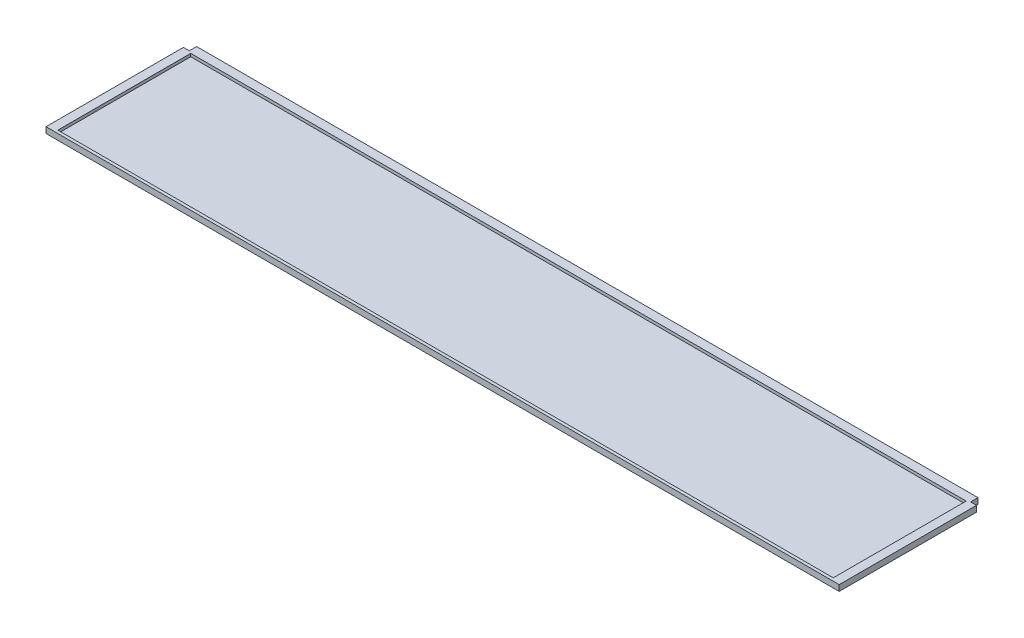
SolidWorks part; units mm, degrees
material "Beech"
ref_plane "Front Plane" through (0, 0, 0) normal (0, 0, 1) x (1, 0, 0)
ref_plane "Top Plane" through (0, 0, 0) normal (0, 1, 0) x (1, 0, 0)
ref_plane "Right Plane" through (0, 0, 0) normal (1, 0, 0) x (0, 0, -1)
sketch "Sketch1" plane through (0, 0, 0) normal (0, 1, 0) x (1, 0, 0)
  line L1 (-118.2851, 60.9681) -> (418.7149, 60.9681)
  line L2 (-118.2851, 60.9681) -> (-118.2851, -37.0319)
  line L3 (-118.2851, -37.0319) -> (418.7149, -37.0319)
  line L4 (418.7149, 60.9681) -> (418.7149, -37.0319)
  dimension "D1" = 98
  dimension "D2" = 537
extrude "Boss-Extrude1" add sketch "Sketch1" along normal blind 4
sketch "Sketch2" plane through (0, 4, 0) normal (0, 1, 0) x (1, 0, 0)
  line L0 (-118.2851, 60.9681) -> (-118.2851, -37.0319) construction
  line L1 (-112.2851, 54.9681) -> (412.7149, 54.9681)
  line L2 (-112.2851, 54.9681) -> (-112.2851, -35.0319)
  line L3 (-112.2851, -35.0319) -> (412.7149, -35.0319)
  line L4 (412.7149, 54.9681) -> (412.7149, -35.0319)
  line L5 (418.7149, -37.0319) -> (418.7149, 60.9681) construction
  line L6 (-118.2851, -37.0319) -> (418.7149, -37.0319) construction
  line L7 (418.7149, 60.9681) -> (-118.2851, 60.9681) construction
  dimension "D1" = 90
  dimension "D2" = 525
  dimension "D3" = 6
  dimension "D4" = 6
  dimension "D5" = 2
  dimension "D6" = 6
extrude "Cut-Extrude1" cut sketch "Sketch2" against normal blind 2
sketch "Sketch3" plane through (0, 4, 0) normal (0, 1, 0) x (1, 0, 0)
  line L1 (-118.2851, 60.9681) -> (-114.2851, 60.9681)
  line L2 (-118.2851, 60.9681) -> (-118.2851, 55.9681)
  line L3 (-118.2851, 55.9681) -> (-114.2851, 55.9681)
  line L4 (-114.2851, 60.9681) -> (-114.2851, 55.9681)
  line L5 (418.7149, 60.9681) -> (414.7149, 60.9681)
  line L6 (418.7149, 60.9681) -> (418.7149, 55.9681)
  line L7 (418.7149, 55.9681) -> (414.7149, 55.9681)
  line L8 (414.7149, 60.9681) -> (414.7149, 55.9681)
  dimension "D1" = 5
  dimension "D2" = 4
  dimension "D3" = 5
  dimension "D4" = 4
extrude "Cut-Extrude2" cut sketch "Sketch3" against normal blind 4
